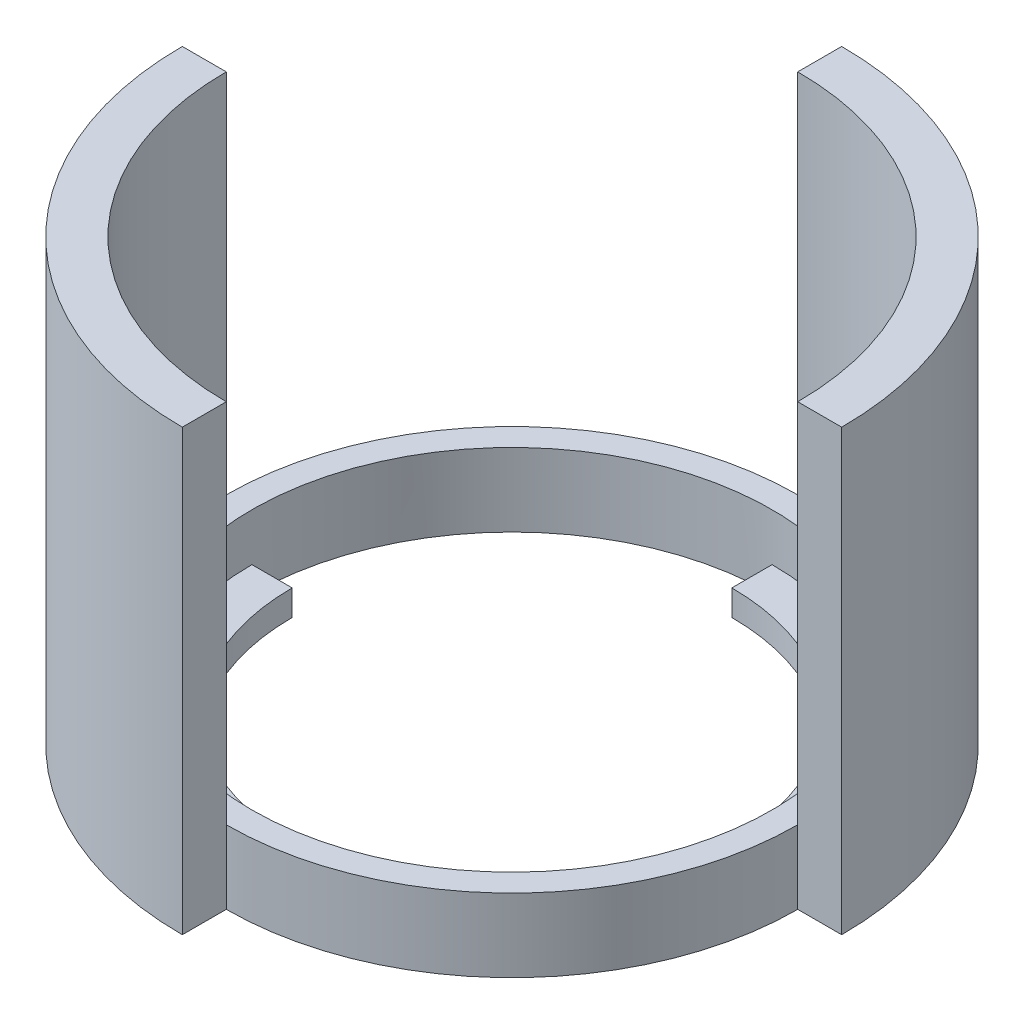
SolidWorks part; units mm, degrees
ref_plane "Plano frontal" through (0, 0, 0) normal (0, 0, 1) x (1, 0, 0)
ref_plane "Plano superior" through (0, 0, 0) normal (0, 1, 0) x (1, 0, 0)
ref_plane "Plano direito" through (0, 0, 0) normal (1, 0, 0) x (0, 0, -1)
sketch "Esboço1" plane through (0, 0, 0) normal (0, 1, 0) x (1, 0, 0)
  circle A0 centre (0, 0) radius 39
  dimension "D1" = 78
extrude "Extrusão1" add sketch "Esboço1" along normal blind 5
sketch "Esboço3" plane through (0, 5, 0) normal (0, 1, 0) x (-1, 0, 0)
  line L0 (45, 0) -> (-45, 0)
  line L1 (0, -45) -> (0, 45)
  arc A0 (45, 0) -> (0, 45) centre (0, 0) ccw
  arc A1 (-45, 0) -> (0, -45) centre (0, 0) ccw
  circle M1 centre (0, 0) radius 39
  dimension "D1" = 90
extrude "Extrusão2" add sketch "Esboço3" along normal blind 50 and the other way blind 5 contours L0 A0 L1 M1 | L0 A1 L1 M1
sketch "Esboço5" plane through (0, 0, 0) normal (0, -1, 0) x (1, 0, 0)
  line L0 (0, 45) -> (0, 39)
  line L1 (-45, 0) -> (-39, 0)
  line L2 (39, 0) -> (45, 0)
  line L3 (0, -39) -> (0, -45)
  arc A0 (-39, 0) -> (0, -39) centre (0, 0) ccw
  arc A1 (0, 45) -> (-45, 0) centre (0, 0) ccw
  arc A2 (0, -45) -> (45, 0) centre (0, 0) ccw
  arc A3 (39, 0) -> (0, 39) centre (0, 0) ccw
extrude "Extrusão11" add sketch "Esboço5" along normal blind 5
sketch "Esboço7" plane through (0, 5, 0) normal (0, 1, 0) x (1, 0, 0)
  circle A1 centre (0, 0) radius 35.5
extrude "Extrusão12" cut sketch "Esboço7" against normal blind 10
sketch "Esboço8" plane through (0, -5, 0) normal (0, -1, 0) x (1, 0, 0)
  line L0 (0, -45) -> (0, -30)
  line L1 (-45, 0) -> (-30, 0)
  line L2 (15, -25.9808) -> (22.5, -38.9711)
  line L3 (25.9808, -15) -> (38.9711, -22.5)
  line L4 (30, 0) -> (45, 0)
  line L5 (0, 30) -> (0, 45)
  line L6 (0, -45) -> (0, -30)
  line L7 (22.5, -38.9711) -> (15, -25.9808)
  line L8 (45, 0) -> (30, 0)
  line L9 (38.9711, -22.5) -> (25.9808, -15)
  line L10 (0, 30) -> (0, 45)
  line L11 (-15, 25.9808) -> (-22.5, 38.9711)
  line L12 (-25.9808, 15) -> (-38.9711, 22.5)
  line L13 (-30, 0) -> (-45, 0)
  arc A0 (0, -35.5) -> (17.75, -30.7439) centre (0, 0) ccw
  arc A1 (0, 45) -> (-45, 0) centre (0, 0) ccw construction
  arc A2 (0, -45) -> (22.5, -38.9711) centre (0, 0) ccw
  arc A3 (0, -39) -> (19.5, -33.775) centre (0, 0) ccw
  arc A4 (0, -30) -> (15, -25.9808) centre (0, 0) ccw
  arc A5 (0, 30) -> (-15, 25.9808) centre (0, 0) ccw
  arc A6 (0, 35.5) -> (-17.75, 30.7439) centre (0, 0) ccw
  arc A7 (0, 39) -> (-19.5, 33.775) centre (0, 0) ccw
  arc A8 (0, 45) -> (-22.5, 38.9711) centre (0, 0) ccw
  arc A9 (25.9808, -15) -> (30, 0) centre (0, 0) ccw
  arc A10 (30.7439, -17.75) -> (35.5, 0) centre (0, 0) ccw
  arc A11 (33.775, -19.5) -> (39, 0) centre (0, 0) ccw
  arc A12 (38.9711, -22.5) -> (45, 0) centre (0, 0) ccw
  arc A13 (-38.9711, 22.5) -> (-45, 0) centre (0, 0) ccw
  arc A14 (-33.775, 19.5) -> (-39, 0) centre (0, 0) ccw
  arc A15 (-30.7439, 17.75) -> (-35.5, 0) centre (0, 0) ccw
  arc A16 (-25.9808, 15) -> (-30, 0) centre (0, 0) ccw
  circle M1 centre (0, 0) radius 35.5
  dimension "D1" = 30
  dimension "D2" = 30
extrude "Extrusão13" add sketch "Esboço8" against normal blind 3.5 contours A5 L5 L11 M1 | A16 L12 L1 M1 | A4 L0 L2 M1 | A9 L3 L4 M1
